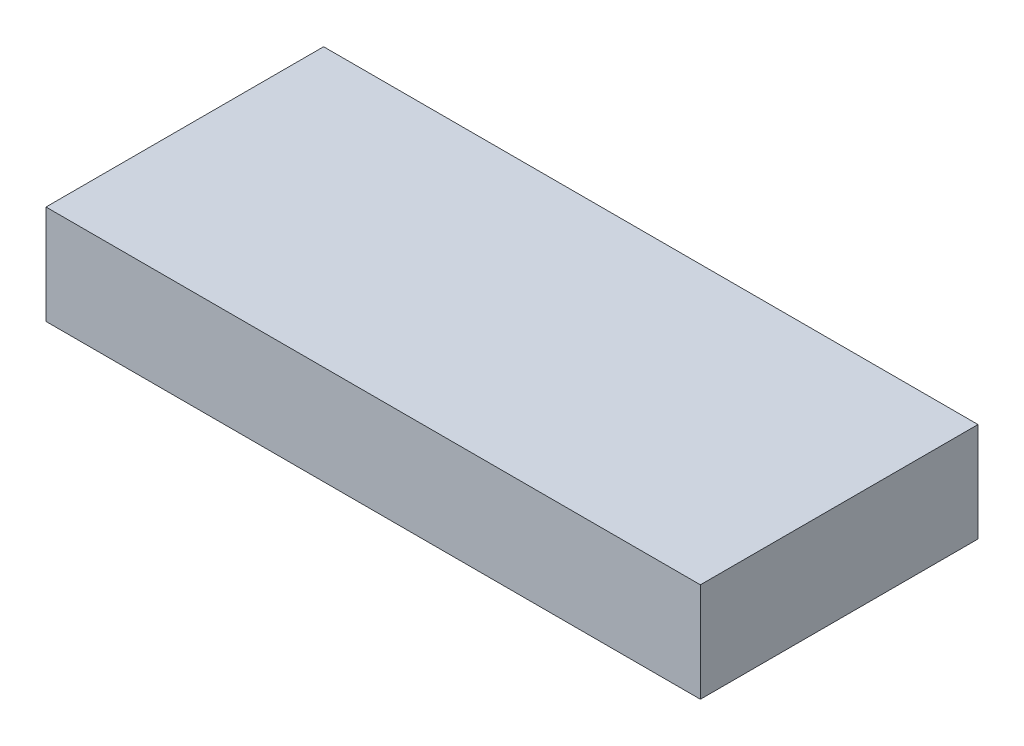
SolidWorks part; units mm, degrees
ref_plane "Front Plane" through (0, 0, 0) normal (0, 0, 1) x (1, 0, 0)
ref_plane "Top Plane" through (0, 0, 0) normal (0, 1, 0) x (1, 0, 0)
ref_plane "Right Plane" through (0, 0, 0) normal (1, 0, 0) x (0, 0, -1)
sketch "Sketch1" plane through (0, 0, 0) normal (0, 1, 0) x (1, 0, 0)
  line L1 (0, 0) -> (28.448, 0)
  line L2 (0, 0) -> (0, 7.1882)
  line L3 (0, 7.1882) -> (28.448, 7.1882)
  line L4 (28.448, 0) -> (28.448, 7.1882)
  dimension "D1" = 7.1882
  dimension "D2" = 28.448
extrude "Boss-Extrude1" add sketch "Sketch1" along normal blind 2.54
sketch "Sketch2" plane through (0, 2.54, 0) normal (0, 1, 0) x (1, 0, 0)
  line L0 (0, 3.5941) -> (28.448, 3.5941) construction
  line L1 (0, 7.1882) -> (0, 0) construction
  line L2 (28.448, 0) -> (28.448, 7.1882) construction
  line L3 (14.224, 7.1882) -> (14.224, 0) construction
  line L4 (28.448, 7.1882) -> (0, 7.1882) construction
  line L5 (0, 0) -> (28.448, 0) construction
  line L7 (-2.54, -3.5179) -> (30.988, -3.5179)
  line L8 (-2.54, -3.5179) -> (-2.54, 10.7061)
  line L9 (-2.54, 10.7061) -> (30.988, 10.7061)
  line L10 (30.988, -3.5179) -> (30.988, 10.7061)
  line L11 (-2.54, -3.5179) -> (30.988, 10.7061) construction
  line L12 (-2.54, 10.7061) -> (30.988, -3.5179) construction
  point P12 (14.224, 3.5941)
  dimension "D1" = 33.528
  dimension "D2" = 14.224
extrude "Boss-Extrude2" add sketch "Sketch2" along normal blind 5.08
